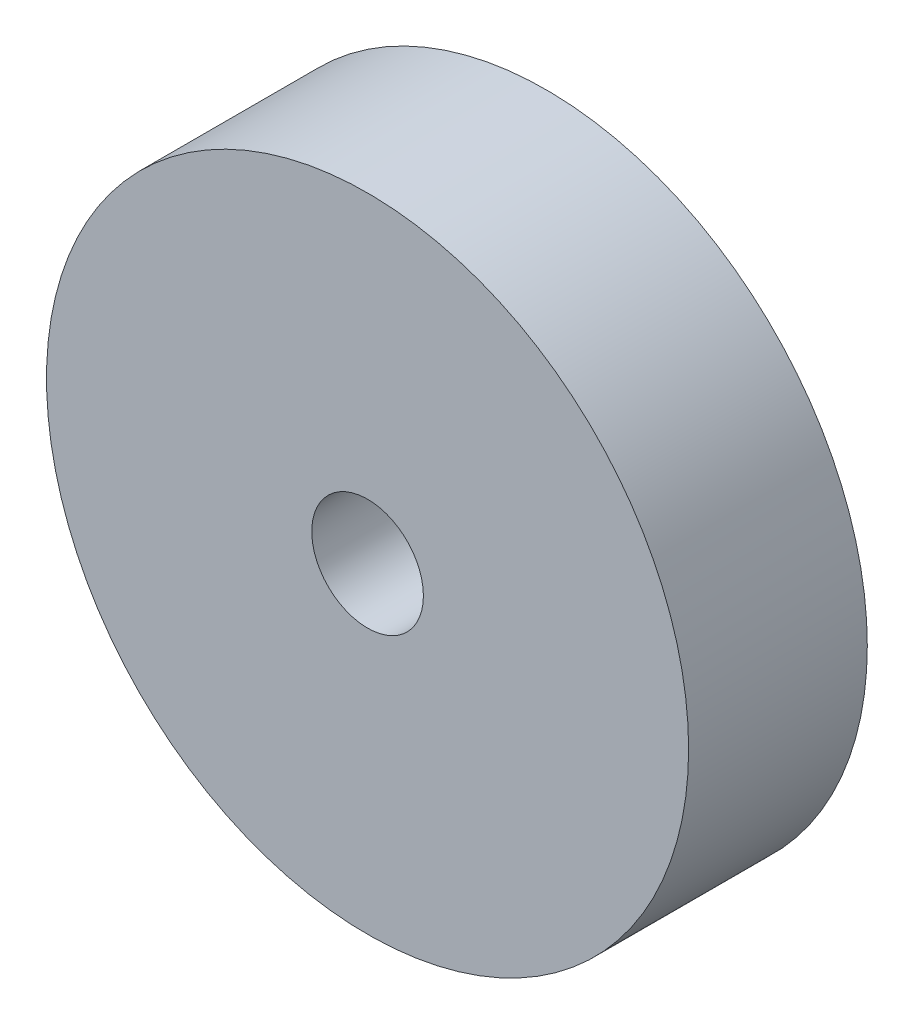
SolidWorks part; units mm, degrees
ref_plane "Front Plane" through (0, 0, 0) normal (0, 0, 1) x (1, 0, 0)
ref_plane "Top Plane" through (0, 0, 0) normal (0, 1, 0) x (1, 0, 0)
ref_plane "Right Plane" through (0, 0, 0) normal (1, 0, 0) x (0, 0, -1)
sketch "Sketch2" plane through (0, 0, 0) normal (0, 0, 1) x (1, 0, 0)
  circle A0 centre (0, 0) radius 36.5125
  circle A1 centre (0, 0) radius 6.35
  dimension "D1" = 73.025
  dimension "D2" = 12.7
extrude "Boss-Extrude1" add sketch "Sketch2" along normal blind 20.32
